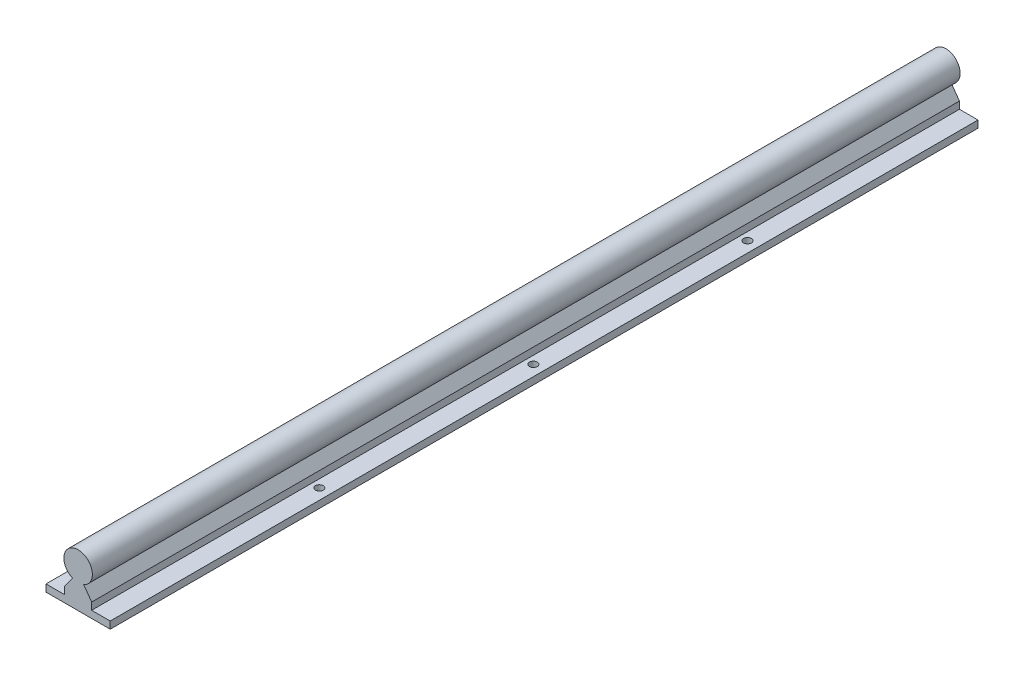
SolidWorks part; units mm, degrees
ref_plane "前视基准面" through (0, 0, 0) normal (0, 0, 1) x (1, 0, 0)
ref_plane "上视基准面" through (0, 0, 0) normal (0, 1, 0) x (1, 0, 0)
ref_plane "右视基准面" through (0, 0, 0) normal (1, 0, 0) x (0, 0, -1)
other "Configuration Table"
sketch "草图1" plane through (0, 0, 0) normal (0, 0, 1) x (1, 0, 0)
  line L0 (-22.5, 0) -> (22.5, 0)
  line L1 (22.5, 0) -> (22.5, 5)
  line L2 (22.5, 5) -> (9.5, 5)
  line L4 (0, 0) -> (0, 17)
  line L5 (3.6756, 17.7) -> (4, 17.7)
  line L6 (0, 0) -> (0, 17)
  line L7 (4, 17.7) -> (9.5, 10)
  line L8 (-9.5, 10) -> (-9.5, 5)
  line L9 (9.5, 10) -> (9.5, 5)
  line L10 (-4, 17.7) -> (-9.5, 10)
  line L11 (-3.6756, 17.7) -> (-4, 17.7)
  line L12 (-22.5, 5) -> (-9.5, 5)
  line L13 (-22.5, 0) -> (-22.5, 5)
  circle A0 centre (0, 27) radius 10
  dimension "D1" = 4
  dimension "D6" = 20
  dimension "D2" = 17.7
  dimension "D3" = 10
  dimension "D4" = 5
  dimension "D5" = 9.5
  dimension "D7" = 27
  dimension "D8" = 45
extrude "凸台-拉伸1" add sketch "草图1" along normal blind 608 contours A0 | A0 L11 L10 L8 L12 L13 L0 L4 | A0 L4 L0 L1 L2 L9 L7 L5
sketch "草图2" plane through (0, 0, 0) normal (0, 1, 0) x (1, 0, 0)
  line L0 (22.5, -304) -> (-22.5, -304)
  line L1 (22.5, -608) -> (22.5, 0) construction
  line L2 (-22.5, -608) -> (-22.5, 0) construction
  line L3 (0, -304) -> (-15, -304)
  line L4 (0, -304) -> (15, -304)
  line L5 (15, -304) -> (15, -454) construction
  circle A0 centre (-15, -304) radius 2.75
  circle A1 centre (15, -304) radius 2.75
  circle A2 centre (15, -454) radius 2.75
  circle A3 centre (-15, -454) radius 2.75
  circle A4 centre (15, -154) radius 2.75
  circle A5 centre (-15, -154) radius 2.75
  circle A6 centre (-15, -154) radius 2.75
  circle A7 centre (15, -154) radius 2.75
  circle A10 centre (-15, 146) radius 2.75
  circle A11 centre (15, 146) radius 2.75
  circle A12 centre (-15, -454) radius 2.75
  circle A13 centre (15, -454) radius 2.75
  circle A16 centre (-15, -754) radius 2.75
  circle A17 centre (15, -754) radius 2.75
  circle A18 centre (15, -4) radius 2.75 [skipped]
  circle A19 centre (-15, -4) radius 2.75 [skipped]
  circle A20 centre (-15, -604) radius 2.75 [skipped]
  circle A21 centre (15, -604) radius 2.75 [skipped]
  dimension "D3" = 2
  dimension "D1" = 30
  dimension "D2" = 15
  dimension "D4" = 150
  dimension "D5" = 2
  dimension "D6" = 4
  dimension "D7" = 4
extrude "切除-拉伸2" cut sketch "草图2" along normal blind 450
